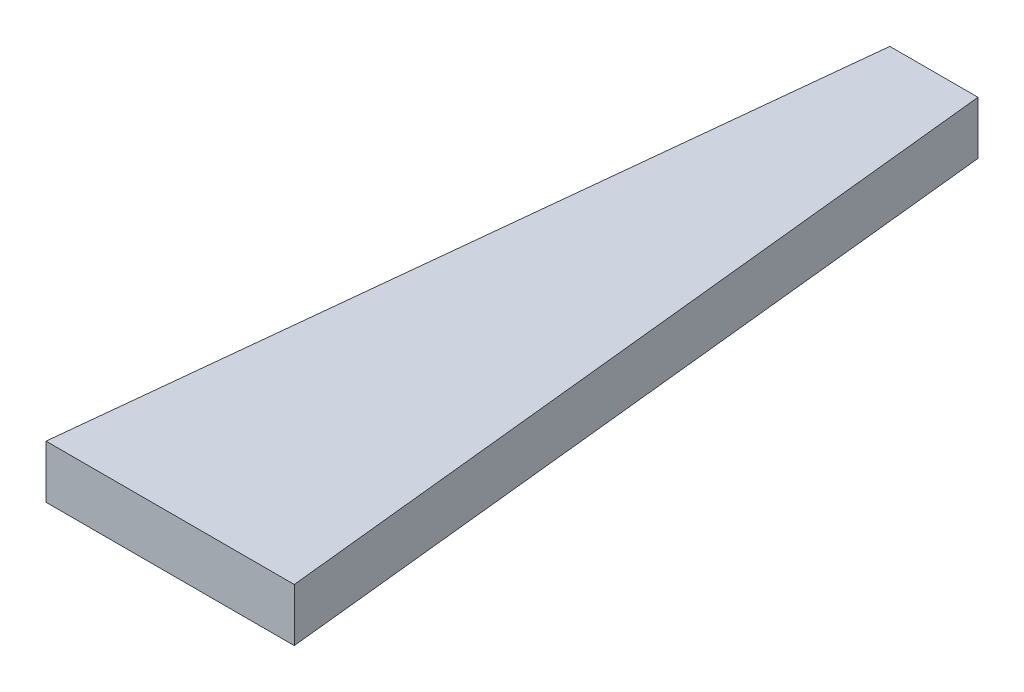
SolidWorks part; units mm, degrees
ref_plane "Front Plane" through (0, 0, 0) normal (0, 0, 1) x (1, 0, 0)
ref_plane "Top Plane" through (0, 0, 0) normal (0, 1, 0) x (1, 0, 0)
ref_plane "Right Plane" through (0, 0, 0) normal (1, 0, 0) x (0, 0, -1)
sketch "Sketch1" plane through (0, 0, 0) normal (0, 1, 0) x (1, 0, 0)
  line L0 (0, 0) -> (9.5997, 91.5813)
  line L1 (9.5997, 91.5813) -> (20.1696, 91.5813)
  line L2 (20.1696, 91.5813) -> (29.7693, 0)
  line L3 (29.7693, 0) -> (0, 0)
  dimension "D1" = 11.968
extrude "Boss-Extrude1" add sketch "Sketch1" along normal blind 6.35
